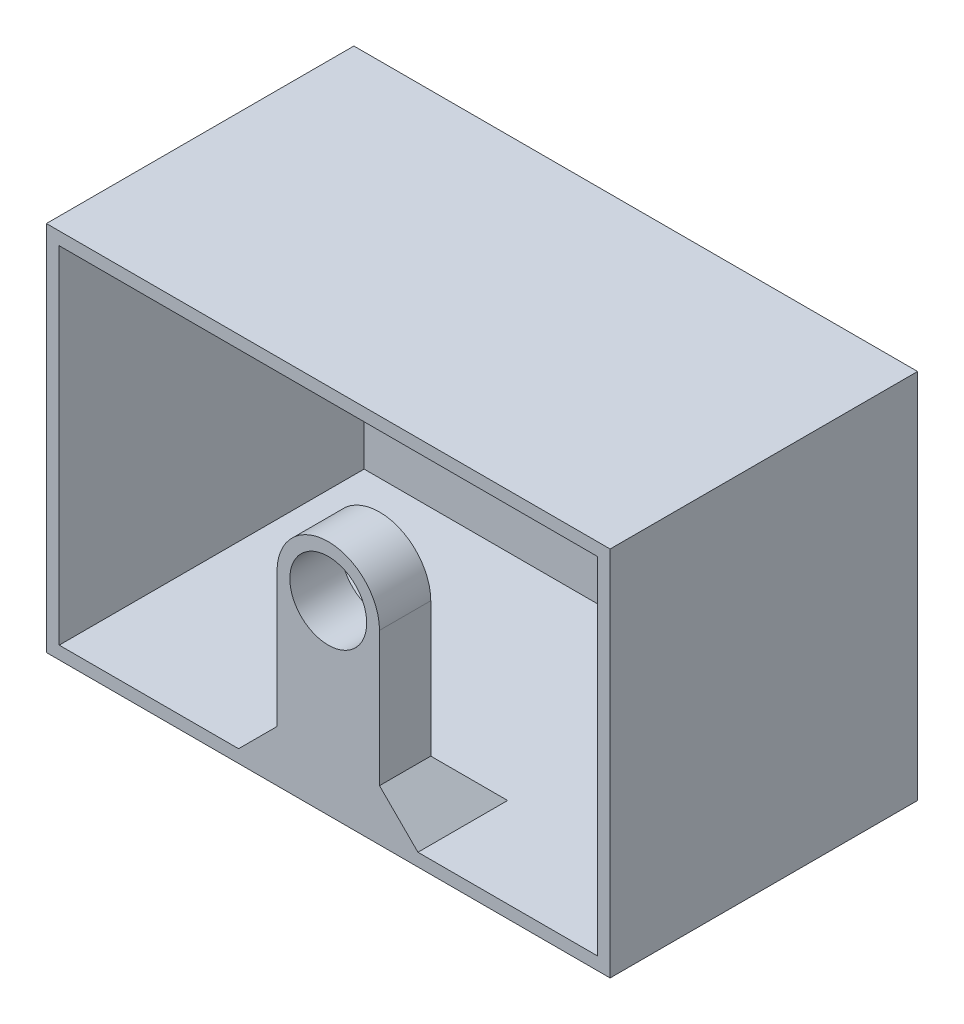
SolidWorks part; units mm, degrees
ref_plane "Plano frontal" through (0, 0, 0) normal (0, 0, 1) x (1, 0, 0)
ref_plane "Plano superior" through (0, 0, 0) normal (0, 1, 0) x (1, 0, 0)
ref_plane "Plano direito" through (0, 0, 0) normal (1, 0, 0) x (0, 0, -1)
sketch "Esboço1" plane through (0, 0, 0) normal (0, 0, 1) x (1, 0, 0)
  line L0 (-110, 0) -> (110, 0) construction
  line L5 (110, -72.5) -> (110, 72.5)
  line L6 (110, 72.5) -> (-110, 72.5)
  line L11 (-110, 72.5) -> (-110, -72.5)
  line L12 (-110, -72.5) -> (110, -72.5)
  line L13 (0, 0) -> (0, 67.5) construction
  line L14 (0, 0) -> (-105, 0) construction
  line L15 (-105, -67.5) -> (-105, 67.5)
  line L16 (0, 0) -> (105, 0) construction
  line L17 (105, -67.5) -> (105, 67.5)
  line L18 (-105, 67.5) -> (105, 67.5)
  line L19 (-105, -67.5) -> (105, -67.5)
  point P0 (0, 0)
  point P6 (0, 0)
  point P8 (110, 0)
  point P10 (0, 72.5)
  point P17 (-105, 0)
  point P21 (105, 0)
  point P23 (0, 67.5)
  dimension "D1" = 210
  dimension "D2" = 5
  dimension "D3" = 135
  dimension "D4" = 5
extrude "Ressalto-extrusão1" add sketch "Esboço1" along normal mid plane 120
sketch "Esboço3" plane through (0, 0, -60) normal (0, 0, -1) x (-1, 0, 0)
  circle A1 centre (0, 0) radius 15
  dimension "D1" = 30
extrude "Ressalto-extrusão3" add sketch "Esboço3" against normal blind 1
sketch "Esboço14" plane through (0, 0, 60) normal (0, 0, 1) x (1, 0, 0)
  line L0 (-20, 0) -> (-20, -67.5)
  line L1 (-105, -67.5) -> (105, -67.5) construction
  line L2 (20, 0) -> (20, -67.5)
  line L3 (-105, -67.5) -> (105, -67.5) construction
  line L4 (-20, -67.5) -> (20, -67.5)
  circle A0 centre (0, 0) radius 15
  arc A1 (20, 0) -> (-20, 0) centre (0, 0) ccw
  dimension "D1" = 30
  dimension "D2" = 40
extrude "Ressalto-extrusão8" add sketch "Esboço14" against normal blind 20
chamfer "Chanfro4" distance 15 angle 45 3 edges at (20, -67.5, 50) (-20, -67.5, 50) (0, -67.5, 40)
